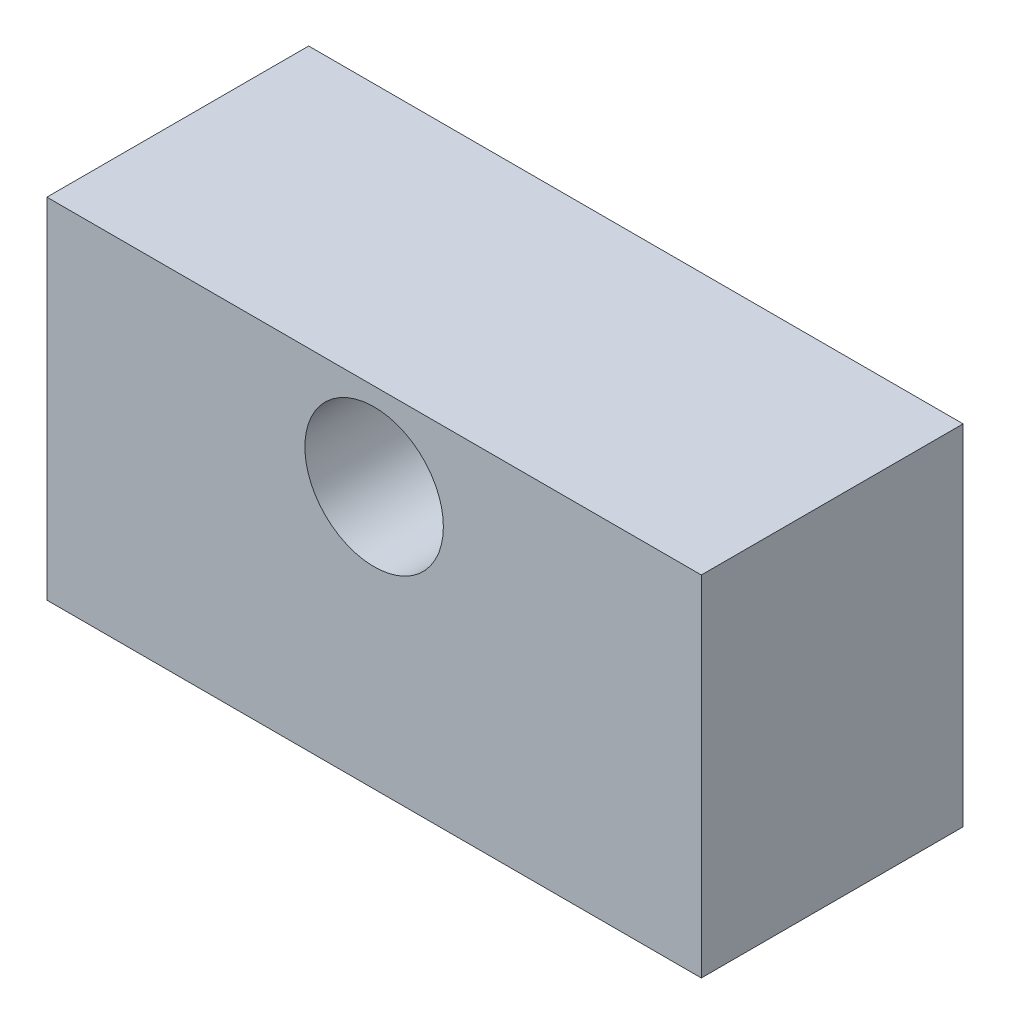
SolidWorks part; units mm, degrees
material "Plain Carbon Steel"
ref_plane "Front Plane" through (0, 0, 0) normal (0, 0, 1) x (1, 0, 0)
ref_plane "Top Plane" through (0, 0, 0) normal (0, 1, 0) x (1, 0, 0)
ref_plane "Right Plane" through (0, 0, 0) normal (1, 0, 0) x (0, 0, -1)
sketch "Sketch1" plane through (0, 0, 0) normal (0, 0, 1) x (1, 0, 0)
  line L0 (-15, -12) -> (15, -12)
  line L1 (15, -12) -> (15, 4)
  line L2 (15, 4) -> (-15, 4)
  line L3 (-15, 4) -> (-15, -12)
  circle A0 centre (0, 0) radius 3.175
  dimension "D1" = 6.35
extrude "Boss-Extrude1" add sketch "Sketch1" along normal blind 12
